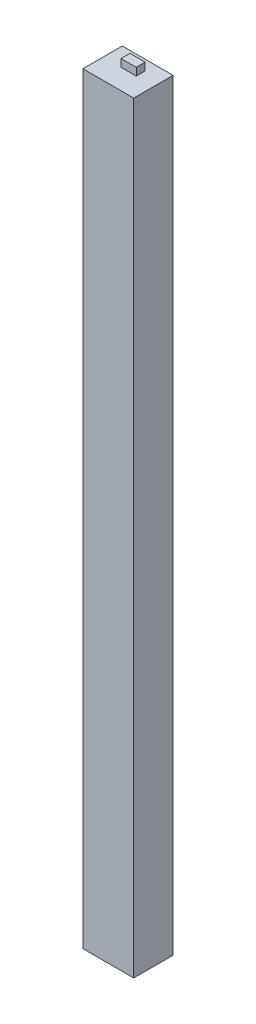
SolidWorks part; units mm, degrees
ref_plane "前视基准面" through (0, 0, 0) normal (0, 0, 1) x (1, 0, 0)
ref_plane "上视基准面" through (0, 0, 0) normal (0, 1, 0) x (1, 0, 0)
ref_plane "右视基准面" through (0, 0, 0) normal (1, 0, 0) x (0, 0, -1)
sketch "草图1" plane through (0, 0, 0) normal (0, 0, 1) x (1, 0, 0)
  line L1 (-10, 150) -> (10, 150)
  line L2 (-10, 150) -> (-10, -150)
  line L3 (-10, -150) -> (10, -150)
  line L4 (10, 150) -> (10, -150)
  line L5 (-10, 150) -> (10, -150) construction
  line L6 (-10, -150) -> (10, 150) construction
  point P0 (0, 0)
  dimension "D1" = 300
  dimension "D2" = 20
extrude "主体" add sketch "草图1" along normal blind 15.5
sketch "草图2" plane through (0, 150, 0) normal (0, 1, 0) x (1, 0, 0)
  line L0 (0, -8.525) -> (0, 8.525) construction
  line L1 (-3, -4) -> (3, -4)
  line L2 (-3, -4) -> (-3, -7.5)
  line L3 (-3, -7.5) -> (3, -7.5)
  line L4 (3, -4) -> (3, -7.5)
  line L5 (-3, -4) -> (3, -7.5) construction
  line L6 (-3, -7.5) -> (3, -4) construction
  line L9 (10, -15.5) -> (-10, -15.5) construction
  line L10 (10, 0) -> (-10, 0) construction
  point P0 (0, -5.75)
  dimension "D1" = 6
  dimension "D2" = 8
  dimension "D3" = 4
extrude "导线" add sketch "草图2" along normal blind 3
